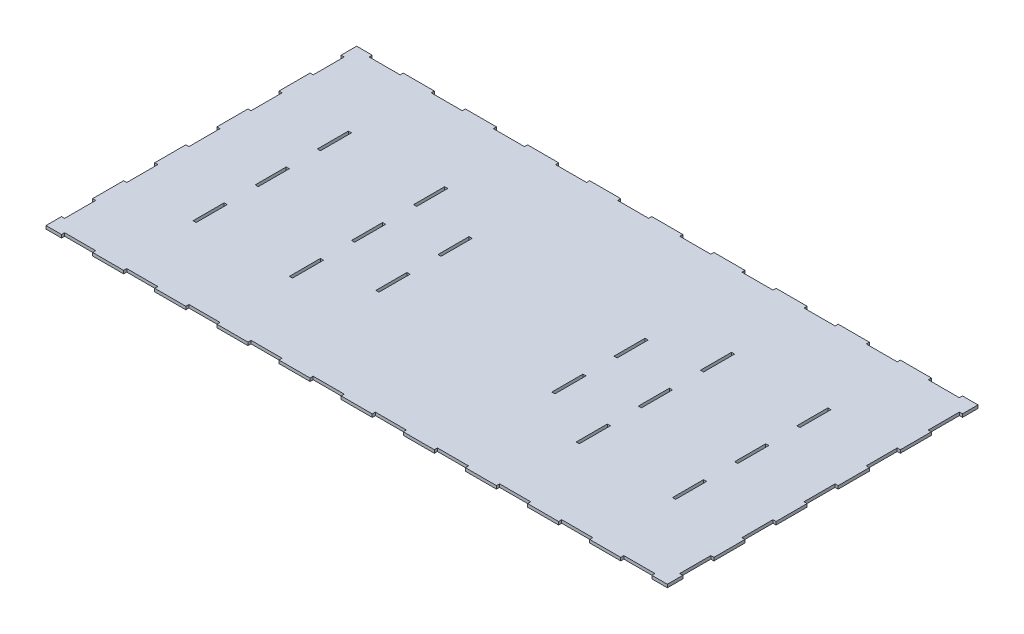
SolidWorks part; units mm, degrees
ref_plane "Front Plane" through (0, 0, 0) normal (0, 0, 1) x (1, 0, 0)
ref_plane "Top Plane" through (0, 0, 0) normal (0, 1, 0) x (1, 0, 0)
ref_plane "Right Plane" through (0, 0, 0) normal (1, 0, 0) x (0, 0, -1)
sketch "Sketch1" plane through (0, 0, 0) normal (0, 1, 0) x (1, 0, 0)
  line L81 (0, 0) -> (600, 0)
  line L82 (0, 0) -> (0, 300)
  line L83 (0, 300) -> (600, 300)
  line L84 (600, 0) -> (600, 300)
  dimension "D1" = 300
  dimension "D2" = 600
extrude "Boss-Extrude1" add sketch "Sketch1" along normal blind 3
sketch "Sketch2" plane through (0, 3, 0) normal (0, 1, 0) x (1, 0, 0)
  line L0 (75, 0) -> (75, 3)
  line L1 (15, 0) -> (45, 0)
  line L2 (15, 0) -> (15, 3)
  line L3 (15, 3) -> (45, 3)
  line L4 (45, 0) -> (45, 3)
  line L5 (75, 0) -> (105, 0)
  line L6 (105, 0) -> (105, 3)
  line L7 (75, 3) -> (105, 3)
  line L8 (135, 0) -> (135, 3)
  line L9 (135, 0) -> (165, 0)
  line L10 (165, 0) -> (165, 3)
  line L11 (135, 3) -> (165, 3)
  line L12 (195, 0) -> (195, 3)
  line L13 (195, 0) -> (225, 0)
  line L14 (225, 0) -> (225, 3)
  line L15 (195, 3) -> (225, 3)
  line L16 (255, 0) -> (255, 3)
  line L17 (255, 0) -> (285, 0)
  line L18 (285, 0) -> (285, 3)
  line L19 (255, 3) -> (285, 3)
  line L20 (315, 0) -> (315, 3)
  line L21 (315, 0) -> (345, 0)
  line L22 (345, 0) -> (345, 3)
  line L23 (315, 3) -> (345, 3)
  line L24 (375, 0) -> (375, 3)
  line L25 (375, 0) -> (405, 0)
  line L26 (405, 0) -> (405, 3)
  line L27 (375, 3) -> (405, 3)
  line L28 (435, 0) -> (435, 3)
  line L29 (435, 0) -> (465, 0)
  line L30 (465, 0) -> (465, 3)
  line L31 (435, 3) -> (465, 3)
  line L32 (495, 0) -> (495, 3)
  line L33 (495, 0) -> (525, 0)
  line L34 (525, 0) -> (525, 3)
  line L35 (495, 3) -> (525, 3)
  line L36 (555, 0) -> (555, 3)
  line L37 (555, 0) -> (585, 0)
  line L38 (585, 0) -> (585, 3)
  line L39 (555, 3) -> (585, 3)
  line L40 (555, 297) -> (585, 297)
  line L41 (0, 150) -> (600, 150) construction
  line L42 (0, 300) -> (0, 0) construction
  line L43 (600, 0) -> (600, 300) construction
  line L44 (585, 300) -> (585, 297)
  line L45 (555, 300) -> (585, 300)
  line L46 (555, 300) -> (555, 297)
  line L47 (495, 297) -> (525, 297)
  line L48 (525, 300) -> (525, 297)
  line L49 (495, 300) -> (525, 300)
  line L50 (495, 300) -> (495, 297)
  line L51 (435, 297) -> (465, 297)
  line L52 (465, 300) -> (465, 297)
  line L53 (435, 300) -> (465, 300)
  line L54 (435, 300) -> (435, 297)
  line L55 (375, 297) -> (405, 297)
  line L56 (405, 300) -> (405, 297)
  line L57 (375, 300) -> (405, 300)
  line L58 (375, 300) -> (375, 297)
  line L59 (315, 297) -> (345, 297)
  line L60 (345, 300) -> (345, 297)
  line L61 (315, 300) -> (345, 300)
  line L62 (315, 300) -> (315, 297)
  line L63 (255, 297) -> (285, 297)
  line L64 (285, 300) -> (285, 297)
  line L65 (255, 300) -> (285, 300)
  line L66 (255, 300) -> (255, 297)
  line L67 (195, 297) -> (225, 297)
  line L68 (225, 300) -> (225, 297)
  line L69 (195, 300) -> (225, 300)
  line L70 (195, 300) -> (195, 297)
  line L71 (135, 297) -> (165, 297)
  line L72 (165, 300) -> (165, 297)
  line L73 (135, 300) -> (165, 300)
  line L74 (135, 300) -> (135, 297)
  line L75 (75, 297) -> (105, 297)
  line L76 (105, 300) -> (105, 297)
  line L77 (75, 300) -> (105, 300)
  line L78 (45, 300) -> (45, 297)
  line L79 (15, 297) -> (45, 297)
  line L80 (15, 300) -> (15, 297)
  line L81 (15, 300) -> (45, 300)
  line L82 (75, 300) -> (75, 297)
  line L83 (0, 0) -> (600, 0) construction
  line L84 (0, 225) -> (0, 195)
  line L85 (0, 285) -> (3, 285)
  line L86 (0, 285) -> (0, 255)
  line L87 (0, 255) -> (3, 255)
  line L88 (3, 285) -> (3, 255)
  line L89 (0, 225) -> (3, 225)
  line L90 (3, 225) -> (3, 195)
  line L91 (0, 195) -> (3, 195)
  line L92 (0, 165) -> (0, 135)
  line L93 (0, 165) -> (3, 165)
  line L94 (3, 165) -> (3, 135)
  line L95 (0, 135) -> (3, 135)
  line L96 (0, 105) -> (0, 75)
  line L97 (0, 105) -> (3, 105)
  line L98 (3, 105) -> (3, 75)
  line L99 (0, 75) -> (3, 75)
  line L100 (0, 45) -> (0, 15)
  line L101 (0, 45) -> (3, 45)
  line L102 (3, 45) -> (3, 15)
  line L103 (0, 15) -> (3, 15)
  line L104 (600, 300) -> (0, 300) construction
  line L105 (300, 300) -> (300, 0) construction
  line L106 (600, 15) -> (597, 15)
  line L107 (597, 45) -> (597, 15)
  line L108 (600, 45) -> (597, 45)
  line L109 (600, 45) -> (600, 15)
  line L110 (600, 75) -> (597, 75)
  line L111 (597, 105) -> (597, 75)
  line L112 (600, 105) -> (597, 105)
  line L113 (600, 105) -> (600, 75)
  line L114 (600, 135) -> (597, 135)
  line L115 (597, 165) -> (597, 135)
  line L116 (600, 165) -> (597, 165)
  line L117 (600, 165) -> (600, 135)
  line L118 (600, 195) -> (597, 195)
  line L119 (597, 225) -> (597, 195)
  line L120 (600, 225) -> (597, 225)
  line L121 (597, 285) -> (597, 255)
  line L122 (600, 255) -> (597, 255)
  line L123 (600, 285) -> (600, 255)
  line L124 (600, 285) -> (597, 285)
  line L125 (600, 225) -> (600, 195)
  dimension "D1" = 30
  dimension "D2" = 3
  dimension "D4" = 30
  dimension "D5" = 15
  dimension "D6" = 30
  dimension "D7" = 3
  dimension "D9" = 15
  dimension "D10" = 30
  dimension "D3" = 10
  dimension "D8" = 5
extrude "Cut-Extrude1" cut sketch "Sketch2" against normal blind 5
sketch "Sketch3" plane through (0, 3, 0) normal (0, 1, 0) x (1, 0, 0)
  line L0 (0, 300) -> (0, 285) construction
  line L1 (3, 135) -> (3, 165) construction
  line L2 (300, 300) -> (300, 0) construction
  line L3 (315, 300) -> (285, 300) construction
  line L4 (285, 0) -> (315, 0) construction
  line L5 (115, 232.5) -> (115, 67.5) construction
  line L6 (135, 300) -> (105, 300) construction
  line L7 (67, 225) -> (70, 225)
  line L8 (67, 225) -> (67, 195)
  line L9 (67, 195) -> (70, 195)
  line L10 (70, 225) -> (70, 195)
  line L11 (67, 165) -> (67, 135)
  line L12 (67, 165) -> (70, 165)
  line L13 (70, 165) -> (70, 135)
  line L14 (67, 135) -> (70, 135)
  line L15 (67, 105) -> (67, 75)
  line L16 (67, 105) -> (70, 105)
  line L17 (70, 105) -> (70, 75)
  line L18 (67, 75) -> (70, 75)
  line L19 (163, 75) -> (160, 75)
  line L20 (160, 105) -> (160, 75)
  line L21 (163, 105) -> (160, 105)
  line L22 (163, 105) -> (163, 75)
  line L23 (163, 135) -> (160, 135)
  line L24 (160, 165) -> (160, 135)
  line L25 (163, 165) -> (160, 165)
  line L26 (163, 165) -> (163, 135)
  line L27 (160, 225) -> (160, 195)
  line L28 (163, 195) -> (160, 195)
  line L29 (163, 225) -> (163, 195)
  line L30 (163, 225) -> (160, 225)
  line L31 (437, 225) -> (440, 225)
  line L32 (437, 225) -> (437, 195)
  line L33 (437, 195) -> (440, 195)
  line L34 (440, 225) -> (440, 195)
  line L35 (437, 165) -> (437, 135)
  line L36 (437, 165) -> (440, 165)
  line L37 (440, 165) -> (440, 135)
  line L38 (437, 135) -> (440, 135)
  line L39 (437, 105) -> (437, 75)
  line L40 (437, 105) -> (440, 105)
  line L41 (440, 105) -> (440, 75)
  line L42 (437, 75) -> (440, 75)
  line L43 (533, 75) -> (530, 75)
  line L44 (530, 105) -> (530, 75)
  line L45 (533, 105) -> (530, 105)
  line L46 (533, 105) -> (533, 75)
  line L47 (533, 135) -> (530, 135)
  line L48 (530, 165) -> (530, 135)
  line L49 (533, 165) -> (530, 165)
  line L50 (533, 165) -> (533, 135)
  line L51 (530, 225) -> (530, 195)
  line L52 (533, 195) -> (530, 195)
  line L53 (533, 225) -> (533, 195)
  line L54 (533, 225) -> (530, 225)
  circle A0 centre (115, 150) radius 82.5 construction
  point P6 (3, 150)
  point P21 (68.5, 165)
  dimension "D1" = 165
  dimension "D2" = 115
  dimension "D3" = 30
  dimension "D4" = 75
  dimension "D5" = 45
  dimension "D6" = 3
  dimension "D8" = 30
  dimension "D7" = 3
extrude "Cut-Extrude2" cut sketch "Sketch3" against normal blind 10
sketch "Sketch4" plane through (0, 3, 0) normal (0, 1, 0) x (1, 0, 0)
  line L0 (300, 300) -> (300, 0) construction
  line L1 (315, 300) -> (285, 300) construction
  line L2 (285, 0) -> (315, 0) construction
  line L3 (163, 195) -> (163, 225) construction
  line L4 (213.5, 195) -> (216.5, 195)
  line L5 (213.5, 195) -> (213.5, 165)
  line L6 (213.5, 165) -> (216.5, 165)
  line L7 (216.5, 195) -> (216.5, 165)
  line L8 (163, 225) -> (160, 225) construction
  line L9 (195, 300) -> (165, 300) construction
  line L10 (213.5, 135) -> (213.5, 105)
  line L11 (213.5, 135) -> (216.5, 135)
  line L12 (216.5, 135) -> (216.5, 105)
  line L13 (213.5, 105) -> (216.5, 105)
  line L15 (386.5, 105) -> (383.5, 105)
  line L16 (383.5, 135) -> (383.5, 105)
  line L17 (386.5, 135) -> (383.5, 135)
  line L18 (386.5, 135) -> (386.5, 105)
  line L19 (383.5, 195) -> (383.5, 165)
  line L20 (386.5, 165) -> (383.5, 165)
  line L21 (386.5, 195) -> (386.5, 165)
  line L22 (386.5, 195) -> (383.5, 195)
  dimension "D1" = 83.5
  dimension "D2" = 105
  dimension "D3" = 2
  dimension "D4" = 30
extrude "Cut-Extrude3" cut sketch "Sketch4" against normal blind 5
